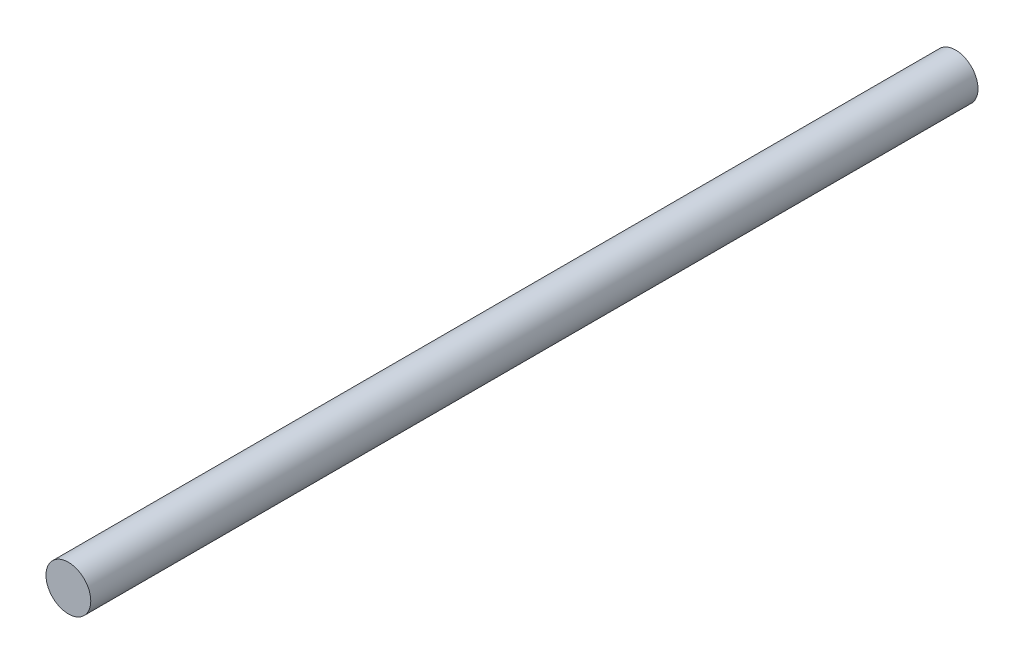
SolidWorks part; units mm, degrees
material "6061 Alloy"
ref_plane "Front Plane" through (0, 0, 0) normal (0, 0, 1) x (1, 0, 0)
ref_plane "Top Plane" through (0, 0, 0) normal (0, 1, 0) x (1, 0, 0)
ref_plane "Right Plane" through (0, 0, 0) normal (1, 0, 0) x (0, 0, -1)
sketch "Sketch1" plane through (0, 0, 0) normal (0, 0, 1) x (1, 0, 0)
  circle A0 centre (0, 0) radius 1.778
  dimension "D1" = 3.556
extrude "Boss-Extrude1" add sketch "Sketch1" against normal blind 70.3805
equation "\"R\"= .070"
equation "\"def\"= .009"
equation "\"F\" = 500"
equation "\"E\"= 10000000"
equation "\"d\"= .12"
equation "\"Area\" = ( \"R\" ^ 2 ) * pi"
equation "\"Length\"= \"E\" * \"Area\" * \"def\" / \"F\""
equation "\"D1@Sketch1\"=\"R\"*2"
equation "\"D1@Boss-Extrude1\"=\"Length\""
